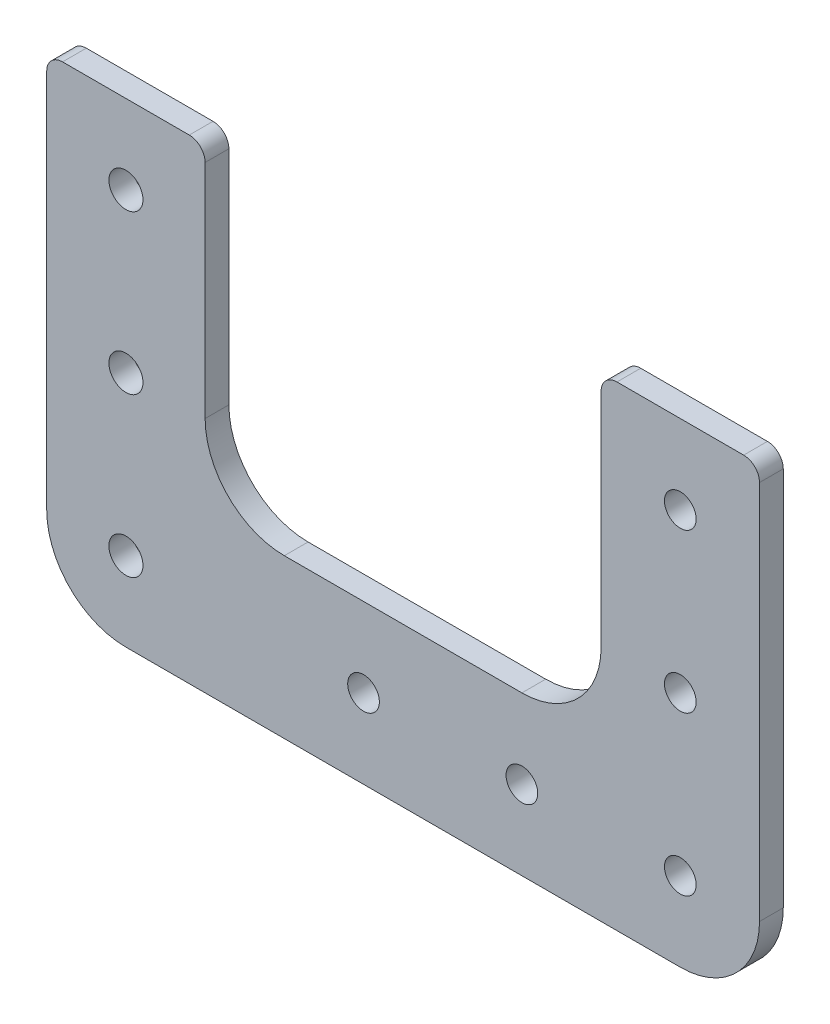
SolidWorks part; units mm, degrees
material "Thornel Mat VMA"
ref_plane "前视基准面" through (0, 0, 0) normal (0, 0, 1) x (1, 0, 0)
ref_plane "上视基准面" through (0, 0, 0) normal (0, 1, 0) x (1, 0, 0)
ref_plane "右视基准面" through (0, 0, 0) normal (1, 0, 0) x (0, 0, -1)
other "Configuration Table"
sketch "草图1" plane through (0, 0, 0) normal (0, 0, 1) x (1, 0, 0)
  line L1 (0, 0) -> (20, 0)
  line L2 (0, 0) -> (0, 60)
  line L3 (0, 60) -> (20, 60)
  line L4 (20, 0) -> (20, 60)
  dimension "D1" = 60
  dimension "D2" = 20
extrude "凸台-拉伸1" add sketch "草图1" along normal blind 3
sketch "草图2" plane through (0, 0, 3) normal (0, 0, 1) x (1, 0, 0)
  line L1 (20, 0) -> (-40, 0)
  line L2 (20, 0) -> (20, 20)
  line L3 (20, 20) -> (-40, 20)
  line L4 (-40, 0) -> (-40, 20)
  dimension "D1" = 20
  dimension "D2" = 60
extrude "凸台-拉伸2" add sketch "草图2" against normal blind 3
sketch "草图3" plane through (0, 0, 3) normal (0, 0, 1) x (1, 0, 0)
  line L0 (0, 20) -> (20, 0) construction
  line L1 (10, 60) -> (10, 10) construction
  line L2 (20, 60) -> (0, 60) construction
  line L3 (10, 10) -> (-40, 10) construction
  line L4 (-40, 20) -> (-40, 0) construction
  circle A0 centre (10, 10) radius 2
  circle A1 centre (10, 30) radius 2
  circle A2 centre (10, 50) radius 2
  circle A4 centre (-10, 10) radius 2
  circle A5 centre (-30, 10) radius 2
  dimension "D1" = 4
  dimension "D3" = 20
  dimension "D2" = 3
extrude "切除-拉伸1" cut sketch "草图3" against normal blind 3
fillet "圆角1" radius 10 2 edges at (20, 0, 1.5) (0, 20, 1.5)
fillet "圆角2" [suppressed] radius 3
sketch "草图4" plane through (0, 0, 3) normal (0, 0, 1) x (1, 0, 0)
  line L0 (-40, 0) -> (10, 0) construction
  line L1 (-70, 60) -> (-50, 60)
  line L2 (-70, 60) -> (-70, 0)
  line L3 (-70, 0) -> (-50, 0)
  line L4 (-50, 60) -> (-50, 0)
  line L5 (20, 10) -> (20, 60) construction
  line L6 (20, 60) -> (0, 60) construction
  line L8 (-40, 20) -> (-50, 20)
  line L9 (-40, 20) -> (-40, 0)
  line L10 (-40, 0) -> (-50, 0)
  line L11 (-50, 20) -> (-50, 0)
  line M16 (-40, 20) -> (-40, 0)
  dimension "D1" = 20
  dimension "D2" = 90
extrude "凸台-拉伸3" add sketch "草图4" against normal through all contours L4 L1 L2 L3 | L10 L8 L4 M16
sketch "草图5" plane through (0, 0, 3) normal (0, 0, 1) x (1, 0, 0)
  line L0 (-60, 60) -> (-60, 0) construction
  line L1 (-70, 60) -> (-50, 60) construction
  line L2 (-70, 0) -> (10, 0) construction
  line L3 (10, 10) -> (-60, 10) construction
  circle A0 centre (-60, 10) radius 2.15
  circle A1 centre (-60, 30) radius 2.15
  circle A2 centre (-60, 50) radius 2.15
  dimension "D1" = 4.3
  dimension "D2" = 20
  dimension "D3" = 20
extrude "切除-拉伸2" cut sketch "草图5" against normal through all
fillet "圆角3" radius 10 2 edges at (-70, 0, 1.5) (-50, 20, 1.5)
fillet "圆角4" radius 2 4 edges at (20, 60, 1.5) (0, 60, 1.5) (-70, 60, 1.5) (-50, 60, 1.5)
